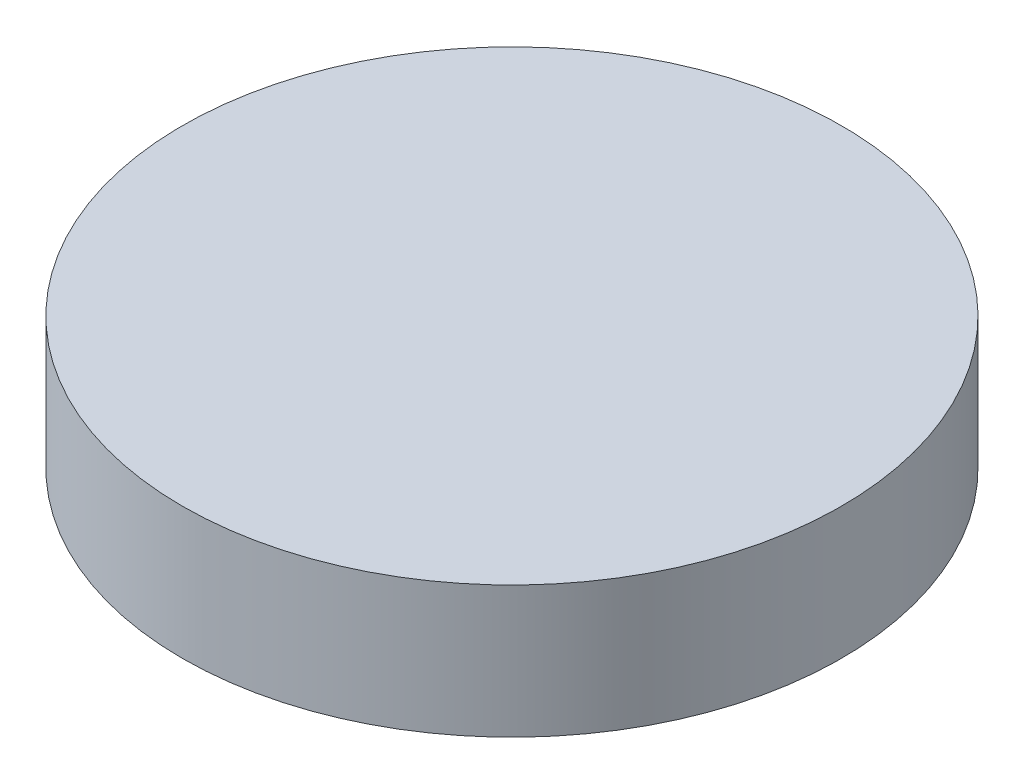
SolidWorks part; units mm, degrees
material "Copper"
ref_plane "Front Plane" through (0, 0, 0) normal (0, 0, 1) x (1, 0, 0)
ref_plane "Top Plane" through (0, 0, 0) normal (0, 1, 0) x (1, 0, 0)
ref_plane "Right Plane" through (0, 0, 0) normal (1, 0, 0) x (0, 0, -1)
sketch "Sketch2" plane through (0, 0, 0) normal (0, 1, 0) x (1, 0, 0)
  circle A0 centre (0, 0) radius 2.5
  dimension "D1" = 5
extrude "Boss-Extrude1" add sketch "Sketch2" along normal blind 1
